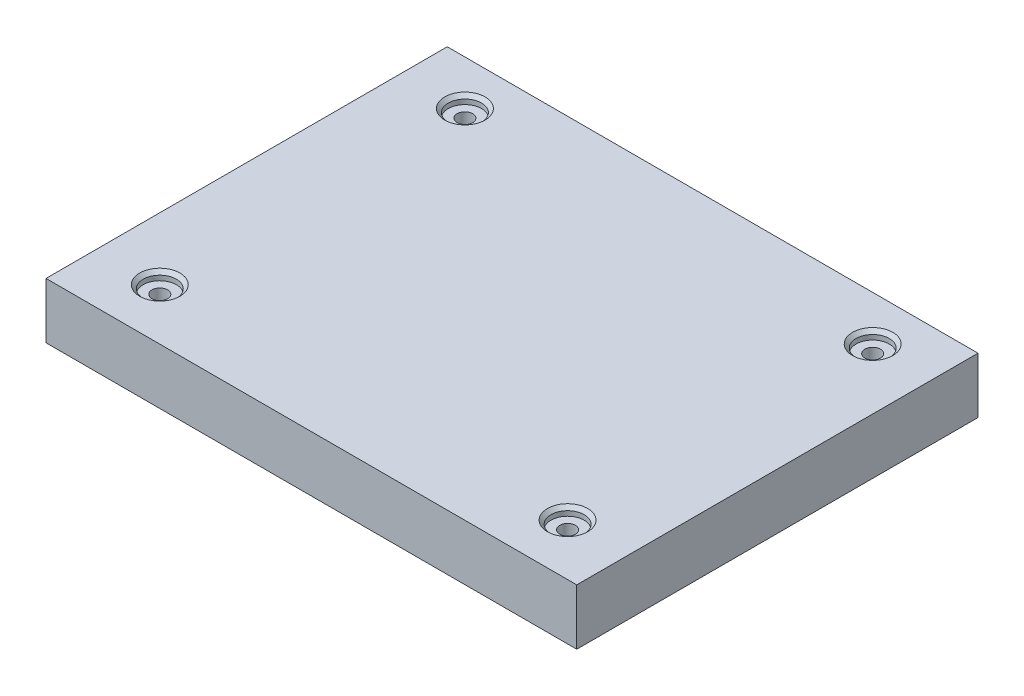
SolidWorks part; units mm, degrees
ref_plane "Front Plane" through (0, 0, 0) normal (0, 0, 1) x (1, 0, 0)
ref_plane "Top Plane" through (0, 0, 0) normal (0, 1, 0) x (1, 0, 0)
ref_plane "Right Plane" through (0, 0, 0) normal (1, 0, 0) x (0, 0, -1)
sketch "Sketch1" plane through (0, 0, 0) normal (0, 1, 0) x (1, 0, 0)
  line L1 (0, 0) -> (95.1693, 0)
  line L2 (0, 0) -> (0, 71.9496)
  line L3 (0, 71.9496) -> (95.1693, 71.9496)
  line L4 (95.1693, 0) -> (95.1693, 71.9496)
extrude "Boss-Extrude1" add sketch "Sketch1" along normal blind 10
hole_wizard "CBORE for #3 Binding Head Machine Screw1" positions "Sketch2" profile "Sketch3" counterbore size "#3" standard "ANSI Inch" end condition through all
sketch "Sketch2" plane through (0, 10, 0) normal (0, 1, 0) x (1, 0, 0)
  line L0 (0, 71.9496) -> (0, 0) construction
  line L1 (95.1693, 71.9496) -> (0, 71.9496) construction
  line L2 (0, 0) -> (95.1693, 0) construction
  point P0 (11.17, 63.9442)
  point P2 (11.17, 9.2372)
  point P4 (84.2963, 63.9396)
  point P6 (84.3, 9.2296)
  point P25 (11.17, 9.2372)
  point P27 (84.3, 9.2296)
  point P29 (84.2963, 63.9396)
  point P31 (11.17, 63.9442)
  point P46 (84.3, 9.2296)
  point P49 (84.3, 9.2296)
  point P50 (11.17, 9.2372)
  point P51 (84.2963, 63.9396)
  point P52 (11.17, 63.9442)
  point P53 (0, 0)
  point P54 (0, 0)
  point P55 (0, 0)
  dimension "D1" = 9.2372
  dimension "D2" = 8.0054
  dimension "D3" = 11.17
  dimension "D4" = 73.1263
  dimension "D5" = 54.707
  dimension "D6" = 73.13
  dimension "D7" = 54.71
  dimension "D8" = 8.01
sketch "Sketch3" plane through (11.17, 10, -63.9442) normal (1, 0, 0) x (0, 0, 1)
  line L0 (0, 0) -> (0, 10)
  line L1 (0, 10) -> (1.397, 10)
  line L3 (1.397, 10) -> (1.397, 1.4986)
  line L4 (2.9769, 1.4986) -> (1.397, 1.4986)
  line L5 (2.9769, 1.4986) -> (2.9769, 0.635)
  line L6 (2.9769, 0.635) -> (3.6119, 0)
  line L7 (3.6119, 0) -> (0, 0)
  line L8 (-2.9769, 0.635) -> (-3.6119, 0) construction
  line L11 (0, -6.35) -> (0, 107.95) construction
  dimension "Thru Hole Dia." = 2.794
  dimension "Thru Hole Depth" = 10
  dimension "C'Bore Dia." = 5.9538
  dimension "C'Bore Depth" = 1.4986
  dimension "Near C'Sink Dia." = 7.2238
  dimension "Near C'Sink Angle" = 90
